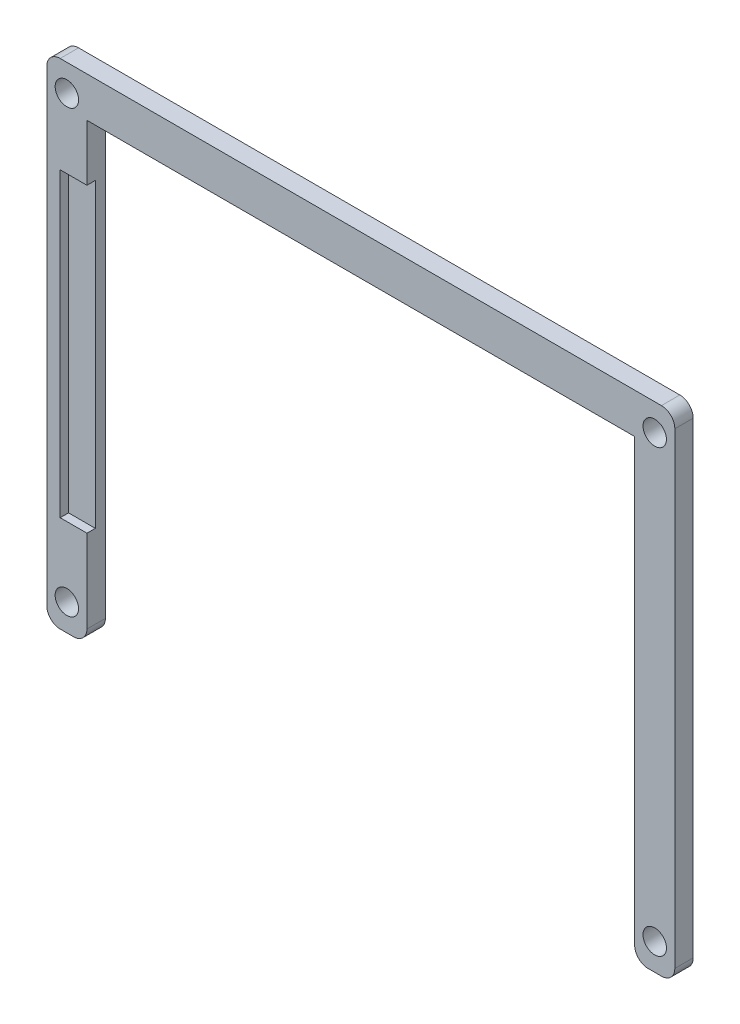
SolidWorks part; units mm, degrees
ref_plane "Front Plane" through (0, 0, 0) normal (0, 0, 1) x (1, 0, 0)
ref_plane "Top Plane" through (0, 0, 0) normal (0, 1, 0) x (1, 0, 0)
ref_plane "Right Plane" through (0, 0, 0) normal (1, 0, 0) x (0, 0, -1)
sketch "Sketch1" plane through (0, 0, 0) normal (0, 0, 1) x (1, 0, 0)
  line L1 (-40.1921, -52.0239) -> (38.8079, -52.0239) construction
  line L2 (-40.1921, -52.0239) -> (-40.1921, -104.0239) construction
  line L3 (-40.1921, -104.0239) -> (38.8079, -104.0239) construction
  line L4 (38.8079, -52.0239) -> (38.8079, -104.0239) construction
  line L5 (-41.5921, -107.9756) -> (-41.5921, -113.3239)
  line L18 (-44.5921, -45.5239) -> (43.2079, -45.5239) construction
  line L19 (-44.5921, -45.5239) -> (-44.5921, -111.3239) construction
  line L20 (-44.5921, -111.3239) -> (43.2079, -111.3239) construction
  line L21 (43.2079, -45.5239) -> (43.2079, -111.3239) construction
  line L22 (-41.5921, -47.5231) -> (40.2079, -47.5231)
  line L23 (-41.5921, -47.5231) -> (-41.5921, -107.9756)
  line L25 (40.2079, -47.5231) -> (40.2079, -107.9756)
  line L26 (-45.5921, -41.5231) -> (44.2079, -41.5231)
  line L27 (-47.5921, -43.5231) -> (-47.5921, -113.3239)
  line L28 (-45.5921, -115.3239) -> (-43.5921, -115.3239)
  line L29 (46.2079, -43.5231) -> (46.2079, -113.3239)
  line L30 (40.2079, -107.9756) -> (40.2079, -113.3239)
  line L31 (42.2079, -115.3239) -> (44.2079, -115.3239)
  circle A2 centre (-44.5921, -45.5239) radius 1.75
  circle A3 centre (43.2079, -45.5239) radius 1.75
  circle A4 centre (43.2079, -111.3239) radius 1.75
  circle A5 centre (-44.5921, -111.3239) radius 1.75
  arc A6 (-45.5921, -41.5231) -> (-47.5921, -43.5231) centre (-45.5921, -43.5231) ccw
  arc A7 (44.2079, -41.5231) -> (46.2079, -43.5231) centre (44.2079, -43.5231) cw
  arc A8 (46.2079, -113.3239) -> (44.2079, -115.3239) centre (44.2079, -113.3239) cw
  arc A9 (42.2079, -115.3239) -> (40.2079, -113.3239) centre (42.2079, -113.3239) cw
  arc A10 (-47.5921, -113.3239) -> (-45.5921, -115.3239) centre (-45.5921, -113.3239) ccw
  arc A11 (-41.5921, -113.3239) -> (-43.5921, -115.3239) centre (-43.5921, -113.3239) cw
  point P7 (-0.6921, -52.0239)
  point P13 (-44.5921, -115.3239)
  point P16 (43.2079, -115.3239)
  point P17 (-0.6921, -47.5231)
  point P26 (40.2079, -115.3239)
  dimension "D21" = 3.5
  dimension "D7" = 2
  dimension "D1" = 79
  dimension "D2" = 52
  dimension "D3" = 6
  dimension "D4" = 6
  dimension "D5" = 6
  dimension "D6" = 4
  dimension "D16" = 87.8
  dimension "D17" = 65.8
  dimension "D19" = 6.5
  dimension "D20" = 7.3
extrude "Boss-Extrude1" add sketch "Sketch1" along normal blind 2.75
sketch "Sketch2" plane through (0, 0, 2.75) normal (0, 0, 1) x (1, 0, 0)
  line L0 (-41.5921, -113.3239) -> (-41.5921, -47.5231) construction
  line L1 (-41.5921, -55.9235) -> (-45.5921, -55.9235)
  line L2 (-41.5921, -55.9235) -> (-41.5921, -100.9235)
  line L3 (-41.5921, -100.9235) -> (-45.5921, -100.9235)
  line L4 (-45.5921, -55.9235) -> (-45.5921, -100.9235)
  line L5 (-47.5921, -43.5231) -> (-47.5921, -113.3239) construction
  point P6 (-45.5921, -78.4235)
  point P9 (-47.5921, -78.4235)
  dimension "D1" = 4
  dimension "D2" = 45
extrude "Cut-Extrude1" cut sketch "Sketch2" against normal blind 1.25
